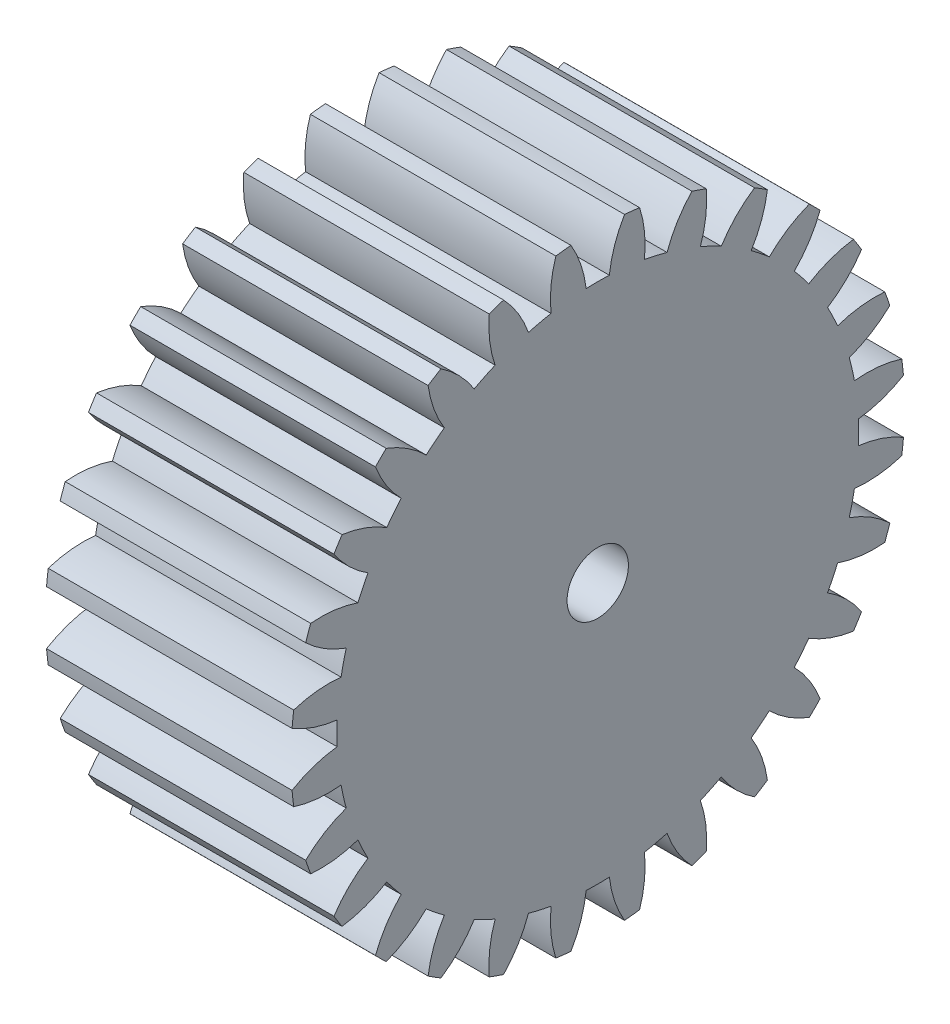
SolidWorks part; units mm, degrees
ref_plane "Plane1" through (0, 0, 0) normal (0, 0, 1) x (1, 0, 0)
ref_plane "Plane2" through (0, 0, 0) normal (0, 1, 0) x (1, 0, 0)
ref_plane "Plane3" through (0, 0, 0) normal (1, 0, 0) x (0, 0, -1)
sketch "HoldingSke" plane through (0, 0, 0) normal (0, 1, 0) x (1, 0, 0)
  line L0 (0, 0) -> (538.2449, -286.1899)
  line L1 (-15, 0) -> (100, 0) construction
  line L2 (0, 0) -> (-2.1039, 2.3779)
  line L3 (0, 0) -> (-11.863, 4.5341)
  line L4 (0, 0) -> (7.6251, 4.0544)
  line L5 (0, 0) -> (-47.5972, -17.7524)
  line L6 (0, 0) -> (-10.5278, -7.1032)
  line L7 (-2.1039, 2.3779) -> (8.8308, 51.9871)
  line L8 (-76.2, 54.61) -> (-72.771, 54.61)
  line L9 (-67.7845, 28.3722) -> (-49.3413, 33.142)
  line L10 (-76.2, 71.12) -> (104.1128, 71.12)
  line L11 (0, 0) -> (-12.7, 0)
  line L12 (-76.2, 101.6) -> (-76.1573, 101.6)
  line L13 (24.9733, 27.94) -> (52.9518, 28.4284)
  line L14 (24.9733, 27.94) -> (25.0241, 27.9398)
  line L15 (24.9733, 27.94) -> (100.4021, 29.52)
  circle A0 centre (0, 0) radius 1.5875
  circle A1 centre (0, 0) radius 13.4959
  circle A2 centre (0, 0) radius 38.1
  circle A3 centre (0, 0) radius 1.5875
  dimension "MHD" = 26.9917
  dimension "Hub_dia" = 76.2
  dimension "Bore" = 3.175
  dimension "MBD" = 3.175
  dimension "Num_teeth" = 28
  dimension "Pitch" = 609.6
  dimension "Overall_len" = 50.8
  dimension "Show_teeth" = 28
  dimension "Thickness" = 12.7
  dimension "OAL" = 50.8001
  dimension "T_dim" = 3.429
  dimension "Ap" = 14.5
  dimension "H" = 19.05
  dimension "Pitch_radius" = 180.3128
  dimension "Width" = 12.7
  dimension "Backlash" = 0.0427
  dimension "Addendum_fac" = 1
  dimension "Dedendum_fac" = 1.2
  dimension "Clearance_fac" = 0.2
  dimension "Dedendum_add" = 0.0508
sketch "BasProSke" plane through (0, 0, 0) normal (0, 1, 0) x (1, 0, 0)
  line L0 (-10, 0) -> (60, 0) construction
  line L1 (0, 0) -> (0, 15.875)
  line L2 (0, 0) -> (12.7, 0)
  line L3 (12.7, 0) -> (12.7, 15.875)
  line L4 (12.7, 15.875) -> (0, 15.875)
  dimension "Thickness" = 12.7
  dimension "Diameter" = 31.75
revolve "Base-Revolve" add sketch "BasProSke" angle 360 about L0
sketch "TooCutSke" plane through (0, 0, 0) normal (1, 0, 0) x (0, 0, -1)
  line L1 (0, 0) -> (0, 107) construction
  line L2 (0, 0) -> (-0.9054, 14.789) construction
  line L3 (0, 0) -> (-3.3136, 29.4086) construction
  line L4 (-0.9054, 14.789) -> (-1.6568, 14.7043) construction
  arc A0 (0.5998, 13.4825) -> (-0.5998, 13.4825) centre (0, 0) ccw
  arc A1 (1.4012, 15.8385) -> (-1.4012, 15.8385) centre (0, 0) ccw
  circle A2 centre (0, 0) radius 14.8167 construction
  circle A3 centre (0, 0) radius 14.3447 construction
  arc A4 (-0.5998, 13.4825) -> (-1.4012, 15.8385) centre (-6.4864, 12.7944) ccw
  arc A5 (1.4012, 15.8385) -> (0.5998, 13.4825) centre (6.4864, 12.7944) ccw
  dimension "Root_dia" = 26.9917
  dimension "Overcut_dia" = 31.8008
  dimension "Pitch_dia" = 29.6333
  dimension "Base_dia" = 28.6894
  dimension "Flank_rad" = 5.9267
  dimension "Half_ang" = 6.429
  dimension "Half_CT" = 0.7561
extrude "ToothCut" cut sketch "TooCutSke" along normal through all
fillet "Breaks" [suppressed] radius 0.0212
fillet "RootFillets" [suppressed] radius 0.2625
pattern_circular "TeethCuts" count 28 every 12.857 about axis through (-10, 0, 0) along (1, 0, 0) of "ToothCut", "RootFillets", "Breaks"
sketch "HubNeaOneSke" plane through (0, 0, 0) normal (-1, 0, 0) x (0, 0, 1)
  circle A0 centre (0, 0) radius 13.4959
  dimension "Diameter" = 26.9917
extrude "HubNearOne" [suppressed] add sketch "HubNeaOneSke" along normal blind 38.1001
sketch "HubNeaBotSke" plane through (0, 0, 0) normal (-1, 0, 0) x (0, 0, 1)
  circle A0 centre (0, 0) radius 13.4959
  dimension "Diameter" = 26.9917
extrude "HubNearBoth" [suppressed] add sketch "HubNeaBotSke" along normal blind 19.05
ref_plane "FarPln" through (12.7, 0, 0) normal (1, 0, 0) x (0, 0, -1)
sketch "HubFarSke" plane through (12.7, 0, 0) normal (1, 0, 0) x (0, 0, -1)
  circle A0 centre (0, 0) radius 13.4959
  dimension "Diameter" = 26.9917
extrude "HubFar" [suppressed] add sketch "HubFarSke" along normal blind 19.05
sketch "BorSke" plane through (0, 0, 0) normal (1, 0, 0) x (0, 0, -1)
  circle A0 centre (0, 0) radius 1.5875
  dimension "Diameter" = 3.175
extrude "Bore" cut sketch "BorSke" along normal mid plane 101.6001
sketch "KeySke" plane through (0, 0, 0) normal (1, 0, 0) x (0, 0, -1)
  line L0 (-0.127, 0) -> (-0.127, 1.8415)
  line L1 (-0.127, 1.8415) -> (0.127, 1.8415)
  line L2 (0.127, 1.8415) -> (0.127, 0)
  line L3 (0, 0) -> (0, 34) construction
  line L4 (-0.127, 0) -> (0.127, 0)
  dimension "Offset" = 1.8415
  dimension "Width" = 0.254
extrude "Keyway" [suppressed] cut sketch "KeySke" along normal mid plane 101.6001
pattern_circular "Keyway2" [suppressed] count 2 every 90 about axis through (-10, 0, 0) along (1, 0, 0)
equation "' \"Pitch@HoldingSke\" = 4"
equation "' \"Num_teeth@HoldingSke\" = 12"
equation "' \"Ap@HoldingSke\" =  20"
equation "' \"Ap@HoldingSke\" = 20"
equation "' \"Width@HoldingSke\" = 0.5"
equation "' \"Hub_dia@HoldingSke\"= 1"
equation "' \"Hub_dia@HoldingSke\" = 1"
equation "' \"Overall_len@HoldingSke\" = 1.0"
equation "' \"Bore@HoldingSke\" = 0.75"
equation "' \"T_dim@HoldingSke\" = 0.85"
equation "' \"Width@KeySke\" = 0.25"
equation "' \"Show_teeth@HoldingSke\" = 13"
equation "' \"Backlash@HoldingSke\" = 0.009"
equation "' \"Addendum_fac@HoldingSke\" = 1.0"
equation "' \"Dedendum_fac@HoldingSke\" = 1.25"
equation "' \"Dedendum_add@HoldingSke\" = 0.00005"
equation "' \"Clearance_fac@HoldingSke\" = 0.25"
equation "' \"Pitch@HoldingSke\" = 0.5"
equation "' \"Num_teeth@HoldingSke\" = 23"
equation "' \"Show_teeth@HoldingSke\" = 23"
equation "' \"Backlash@HoldingSke\" = 0.0375"
equation "\"Overcut_dia@TooCutSke\" = (\"Num_teeth@HoldingSke\" + 2 * \"Addendum_fac@HoldingSke\") / \"Pitch@HoldingSke\" + 0.002"
equation "\"Pitch_dia@TooCutSke\" = \"Num_teeth@HoldingSke\" / \"Pitch@HoldingSke\""
equation "\"Base_dia@TooCutSke\" = \"Num_teeth@HoldingSke\" / \"Pitch@HoldingSke\" * cos((\"Ap@HoldingSke\"  * 3.14159265 / 180))"
equation "\"Root_dia@TooCutSke\" = (\"Num_teeth@HoldingSke\" + 2) / \"Pitch@HoldingSke\" - 2 * (\"Addendum_fac@HoldingSke\" + \"Dedendum_fac@HoldingSke\") / \"Pitch@HoldingSke\" - \"Dedendum_add@HoldingSke\" * 2"
equation "\"Half_ang@TooCutSke\" = 180 / \"Num_teeth@HoldingSke\""
equation "\"Half_CT@TooCutSke\" = \"Num_teeth@HoldingSke\" / \"Pitch@HoldingSke\" * sin((3.14159265 / 2 / \"Num_teeth@HoldingSke\")) / 2 - 7 * \"Backlash@HoldingSke\" / 4"
equation "\"Flank_rad@TooCutSke\" = \"Num_teeth@HoldingSke\" / \"Pitch@HoldingSke\" / 5"
equation "\"Radius@RootFillets\" = \"Clearance_fac@HoldingSke\" / \"Pitch@HoldingSke\" + \"Dedendum_add@HoldingSke\""
equation "\"Break_rad@Breaks\" = 0.02 / \"Pitch@HoldingSke\""
equation "\"Thickness@HoldingSke\" = \"Width@HoldingSke\""
equation "\"OAL@HoldingSke\" = \"Thickness@HoldingSke\""
equation "\"MHD@HoldingSke\" = (\"Num_teeth@HoldingSke\" + 2) / \"Pitch@HoldingSke\" - 2 * (\"Addendum_fac@HoldingSke\" + \"Dedendum_fac@HoldingSke\")  / \"Pitch@HoldingSke\" - \"Dedendum_add@HoldingSke\" * 2"
equation "\"MBD@HoldingSke\" = (\"Num_teeth@HoldingSke\" + 2) / \"Pitch@HoldingSke\" - 2 * (\"Addendum_fac@HoldingSke\" + \"Dedendum_fac@HoldingSke\")  / \"Pitch@HoldingSke\" - \"Dedendum_add@HoldingSke\" * 2 - 0.002"
equation "\"MHD@HoldingSke\" = ((sgn( \"MHD@HoldingSke\" - \"Hub_dia@HoldingSke\" )-1)*( \"MHD@HoldingSke\" - \"Hub_dia@HoldingSke\" ))/-2+ \"Hub_dia@HoldingSke\""
equation "\"MBD@HoldingSke\" = ((sgn( \"MBD@HoldingSke\" - \"Bore@HoldingSke\" )-1)*( \"MBD@HoldingSke\" - \"Bore@HoldingSke\" ))/-2+ \"Bore@HoldingSke\""
equation "\"OAL@HoldingSke\" = ((sgn( \"OAL@HoldingSke\" - \"Overall_len@HoldingSke\" )+1)*( \"OAL@HoldingSke\" - \"Overall_len@HoldingSke\" ))/2 + \"Overall_len@HoldingSke\" + 0.000002"
equation "\"Num_teeth@TeethCuts\" = int( \"Show_teeth@HoldingSke\" ) + 1"
equation "\"Num_teeth@TeethCuts\" = ((sgn( \"Num_teeth@TeethCuts\" - \"Num_teeth@HoldingSke\" )-1)*( \"Num_teeth@TeethCuts\" - \"Num_teeth@HoldingSke\" ))/-2+ \"Num_teeth@HoldingSke\""
equation "\"Num_teeth@TeethCuts\" = ((sgn( \"Num_teeth@TeethCuts\" - 2.0)+1)*( \"Num_teeth@TeethCuts\" - 2.0))/2 +2.0"
equation "\"Angle@TeethCuts\" = 360.0 / \"Num_teeth@HoldingSke\""
equation "\"Diameter@BasProSke\" = (\"Num_teeth@HoldingSke\" + 2 * \"Addendum_fac@HoldingSke\") / \"Pitch@HoldingSke\""
equation "\"Thickness@BasProSke\"  = \"Thickness@HoldingSke\""
equation "' \"Fillet_rad@BasProSke\" =  \"Thickness@HoldingSke\" * 0.05"
equation "' \"Fillet_rad@BasProSke\" = \"Thickness@HoldingSke\" * 0.05"
equation "\"MHD@HoldingSke\" = ((sgn( \"MHD@HoldingSke\" - \"Root_dia@TooCutSke\" )-1)*( \"MHD@HoldingSke\" - \"Root_dia@TooCutSke\" ))/-2+ \"Root_dia@TooCutSke\""
equation "\"Diameter@HubNeaOneSke\" = \"MHD@HoldingSke\""
equation "\"Length@HubNearOne\" = \"OAL@HoldingSke\" - \"Thickness@BasProSke\""
equation "\"Diameter@HubNeaBotSke\" = \"MHD@HoldingSke\""
equation "\"Length@HubNearBoth\" = ( \"OAL@HoldingSke\" - \"Thickness@BasProSke\" ) / 2.0"
equation "\"Thickness@FarPln\" = \"Thickness@BasProSke\""
equation "\"Diameter@HubFarSke\" = \"MHD@HoldingSke\""
equation "\"Length@HubFar\" = ( \"OAL@HoldingSke\" - \"Thickness@BasProSke\" ) / 2.0"
equation "\"Diameter@BorSke\" = \"MBD@HoldingSke\""
equation "\"D1@Bore\" = \"OAL@HoldingSke\" * 2.0"
equation "\"D1@Keyway\" = \"OAL@HoldingSke\" * 2.0"
equation "\"Offset@KeySke\" = \"T_dim@HoldingSke\" - \"MBD@HoldingSke\" / 2.0"
